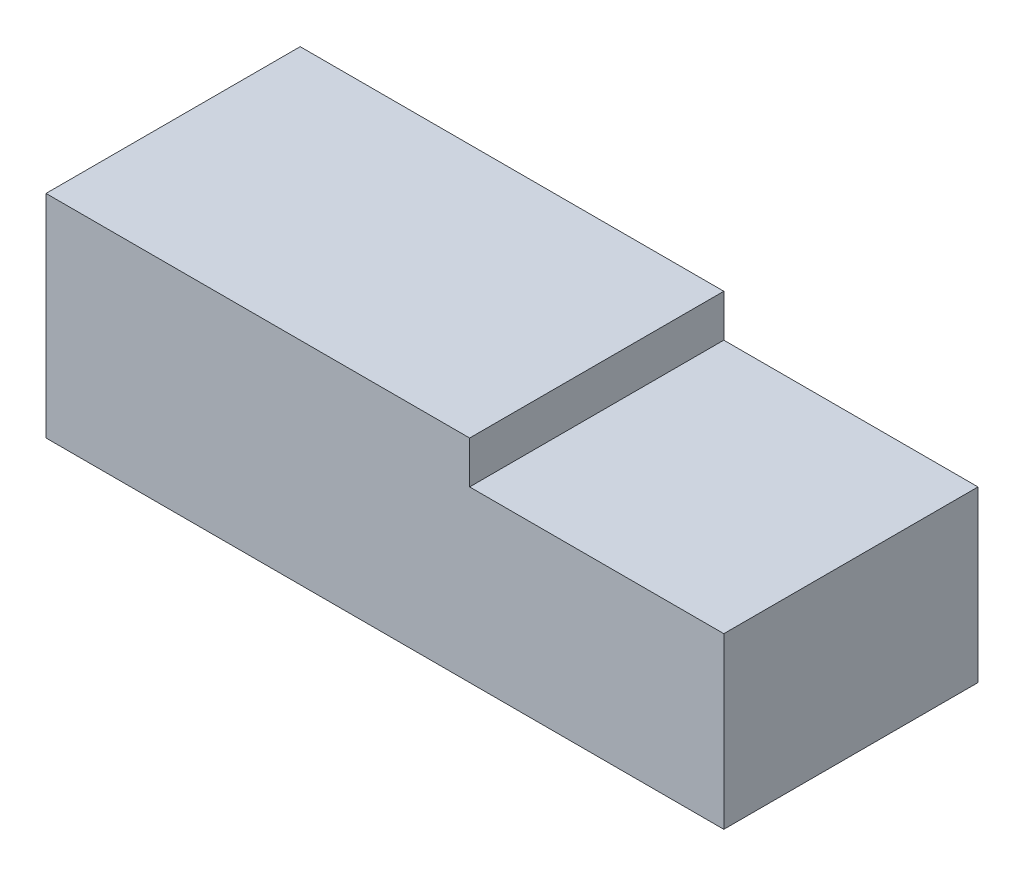
SolidWorks part; units mm, degrees
ref_plane "Front Plane" through (0, 0, 0) normal (0, 0, 1) x (1, 0, 0)
ref_plane "Top Plane" through (0, 0, 0) normal (0, 1, 0) x (1, 0, 0)
ref_plane "Right Plane" through (0, 0, 0) normal (1, 0, 0) x (0, 0, -1)
sketch "Sketch1" plane through (0, 0, 0) normal (0, 0, 1) x (1, 0, 0)
  line L0 (0, 0) -> (101.6, 0)
  line L1 (101.6, 0) -> (101.6, 25.4)
  line L2 (101.6, 25.4) -> (63.5, 25.4)
  line L3 (63.5, 25.4) -> (63.5, 31.75)
  line L4 (63.5, 31.75) -> (0, 31.75)
  line L5 (0, 31.75) -> (0, 0)
  dimension "D1" = 101.6
  dimension "D2" = 25.4
  dimension "D3" = 38.1
  dimension "D4" = 31.75
extrude "Boss-Extrude1" add sketch "Sketch1" along normal blind 38.1 contours L4 L5 L0 L1 L2 L3
